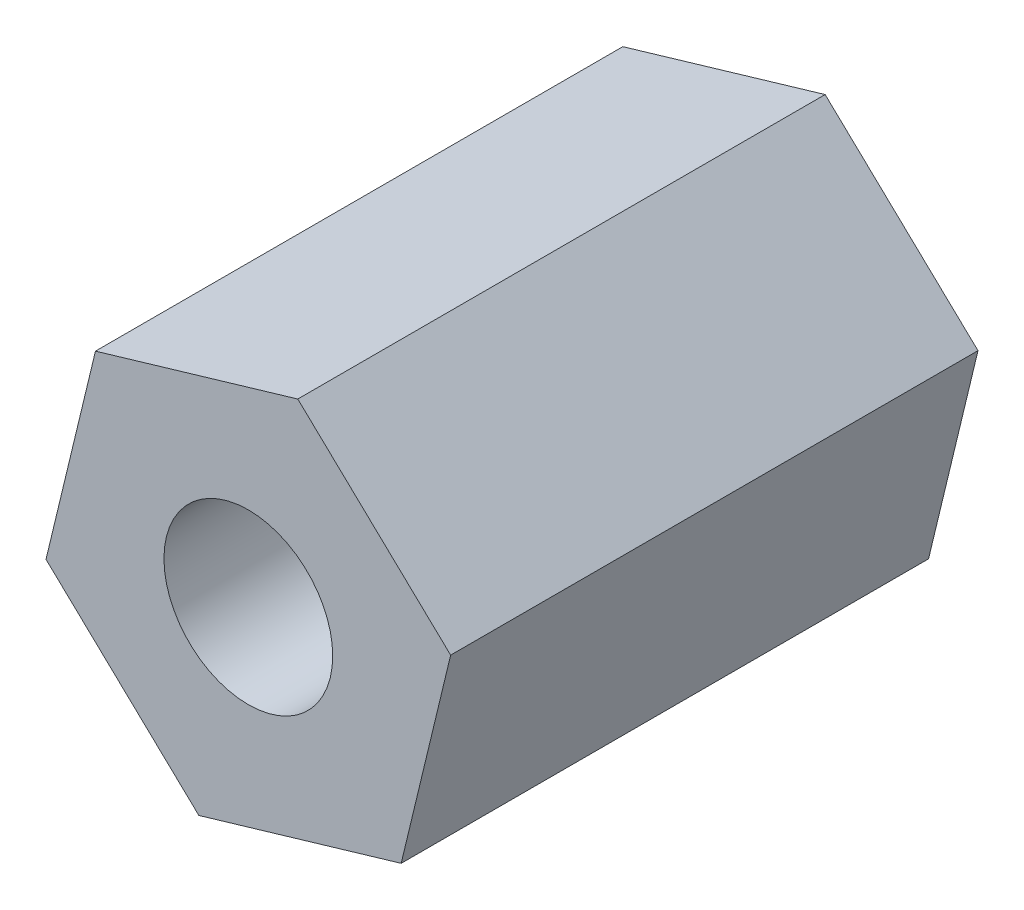
SolidWorks part; units mm, degrees
ref_plane "前视基准面" through (0, 0, 0) normal (0, 0, 1) x (1, 0, 0)
ref_plane "上视基准面" through (0, 0, 0) normal (0, 1, 0) x (1, 0, 0)
ref_plane "右视基准面" through (0, 0, 0) normal (1, 0, 0) x (0, 0, -1)
sketch "草图1" plane through (0, 0, 0) normal (0, 0, 1) x (1, 0, 0)
  line L1 (2.8985, -2.7566) -> (3.8365, 1.1319)
  line L2 (3.8365, 1.1319) -> (0.938, 3.8885)
  line L3 (0.938, 3.8885) -> (-2.8985, 2.7566)
  line L4 (-2.8985, 2.7566) -> (-3.8365, -1.1319)
  line L5 (-3.8365, -1.1319) -> (-0.938, -3.8885)
  line L6 (-0.938, -3.8885) -> (2.8985, -2.7566)
  circle A1 centre (0, 0) radius 3.4641 construction
extrude "凸台-拉伸1" add sketch "草图1" along normal blind 10
sketch "草图2" plane through (0, 0, 0) normal (0, 0, 1) x (1, 0, 0)
  circle A0 centre (0, 0) radius 1.6
extrude "切除-拉伸1" cut sketch "草图2" along normal blind 48
